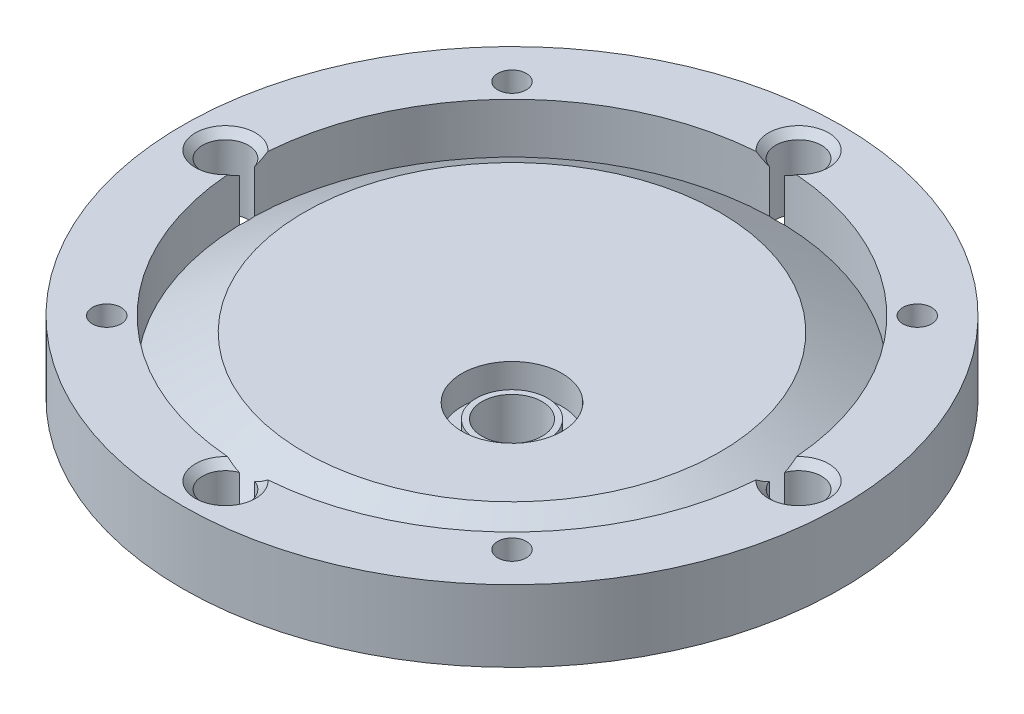
SolidWorks part; units mm, degrees
ref_plane "前视基准面" through (0, 0, 0) normal (0, 0, 1) x (1, 0, 0)
ref_plane "上视基准面" through (0, 0, 0) normal (0, 1, 0) x (1, 0, 0)
ref_plane "右视基准面" through (0, 0, 0) normal (1, 0, 0) x (0, 0, -1)
other "Configuration Table"
sketch "草图1" plane through (0, 0, 0) normal (0, 1, 0) x (1, 0, 0)
  circle A0 centre (0, 0) radius 23
  dimension "D1" = 46
extrude "凸台-拉伸1" add sketch "草图1" along normal blind 5
sketch "草图2" plane through (0, 5, 0) normal (0, 1, 0) x (1, 0, 0)
  circle A0 centre (0, 0) radius 20 construction
  circle A1 centre (0, 20) radius 1.6
  circle A2 centre (20.001, 0.001) radius 1.6
  circle A3 centre (0.002, -20) radius 1.6
  circle A4 centre (-19.999, -0.001) radius 1.6
  point P14 (0.001, 0)
  dimension "D1" = 40
  dimension "D2" = 3.2
  dimension "D3" = 4
extrude "切除-拉伸1" cut sketch "草图2" against normal through all
sketch "草图3" plane through (0, 5, 0) normal (0, 1, 0) x (1, 0, 0)
  line L0 (0, 20) -> (0, 0) construction
  line L1 (0, 0) -> (14.1421, 14.1421) construction
  circle A0 centre (14.1421, 14.1421) radius 1
  circle A1 centre (14.1421, -14.1421) radius 1
  circle A2 centre (-14.1421, -14.1421) radius 1
  circle A3 centre (-14.1421, 14.1421) radius 1
  point P15 (0, 0)
  dimension "D1" = 2
  dimension "D2" = 45
  dimension "D3" = 20
  dimension "D4" = 4
extrude "切除-拉伸2" cut sketch "草图3" against normal through all
sketch "草图4" plane through (0, 0, 0) normal (0, 0, 1) x (1, 0, 0)
  line L0 (0, 0) -> (0, 5) construction
  line L1 (23, 5) -> (-23, 5) construction
  line L2 (14.5, 5) -> (14.5, 4)
  line L3 (14.5, 4) -> (18.5, 1.5)
  line L4 (18.5, 1.5) -> (18.5, 5)
  line L6 (18.5, 5) -> (14.5, 5)
  line L7 (14.5, 4) -> (0, 4)
  line L9 (0, 4) -> (0, 5)
  line L10 (0, 5) -> (14.5, 5)
  dimension "D1" = 14.5
  dimension "D2" = 18.5
  dimension "D3" = 2.5
  dimension "D4" = 1
revolve "切除-旋转1" cut sketch "草图4" angle 360 about L0
sketch "草图5" plane through (0, 4, 0) normal (0, 1, 0) x (1, 0, 0)
  line L0 (0, 0) -> (4.2426, -4.2426) construction
  line L4 (4.2426, -4.2426) -> (0, 0) construction
  line L5 (0, 0) -> (0, -7.0292)
  circle A1 centre (4.2426, -4.2426) radius 2.1
  dimension "D2" = 4.2
  dimension "D3" = 6
  dimension "D7" = 45
extrude "切除-拉伸3" cut sketch "草图5" against normal through all contours A1
sketch "草图6" plane through (0, 4, 0) normal (0, 1, 0) x (1, 0, 0)
  circle A0 centre (4.2426, -4.2426) radius 2.5
  dimension "D1" = 5
extrude "切除-拉伸-薄壁1" cut sketch "草图6" against normal blind 2 thin
sketch "草图7" plane through (0, 4, 0) normal (0, 1, 0) x (1, 0, 0)
  circle A0 centre (4.2426, -4.2426) radius 3.5
  dimension "D1" = 7
extrude "切除-拉伸4" cut sketch "草图7" against normal blind 1
chamfer "倒角1" distance 0.5 angle 45 4 edges at (21.601, 5, -0.0011) (0, 5, -21.6) (-21.599, 5, 0.0011) (0.0022, 5, 21.6)
